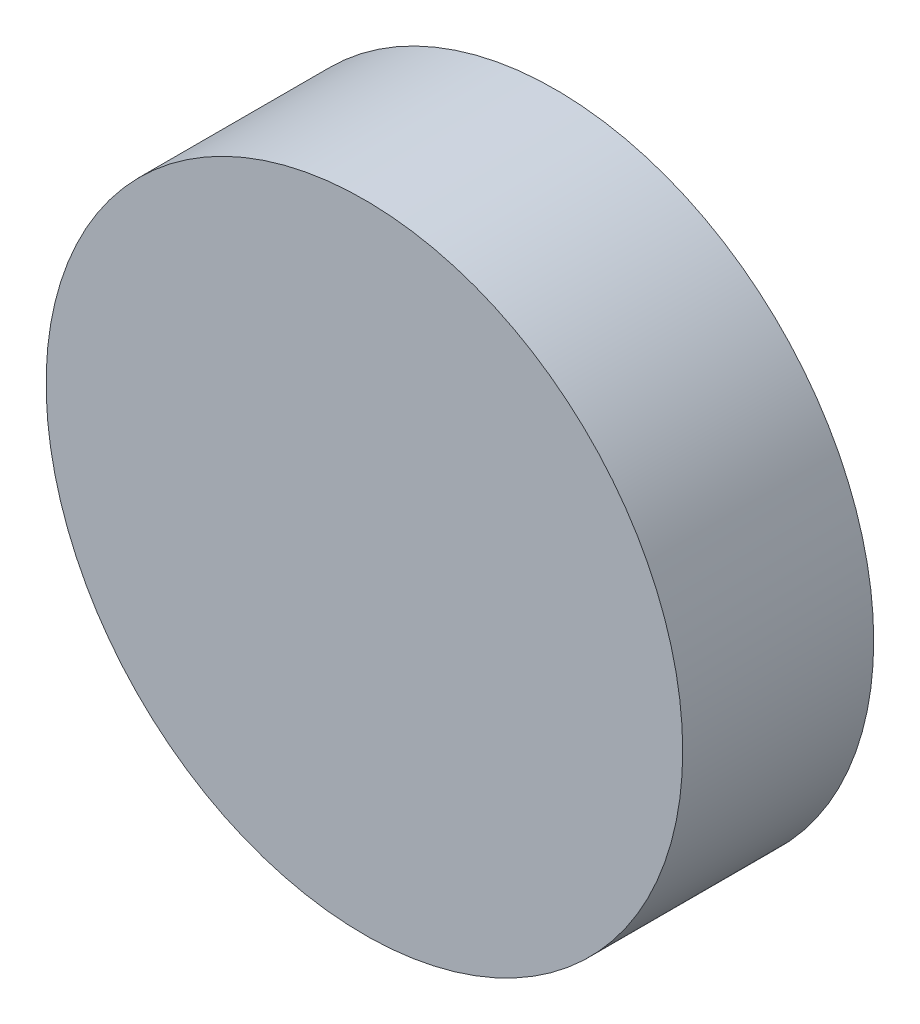
SolidWorks part; units mm, degrees
ref_plane "Front Plane" through (0, 0, 0) normal (0, 0, 1) x (1, 0, 0)
ref_plane "Top Plane" through (0, 0, 0) normal (0, 1, 0) x (1, 0, 0)
ref_plane "Right Plane" through (0, 0, 0) normal (1, 0, 0) x (0, 0, -1)
sketch "Sketch1" plane through (0, 0, 0) normal (0, 0, 1) x (1, 0, 0)
  circle A0 centre (0, 0) radius 5
  dimension "D1" = 10
extrude "Boss-Extrude1" add sketch "Sketch1" along normal blind 3
